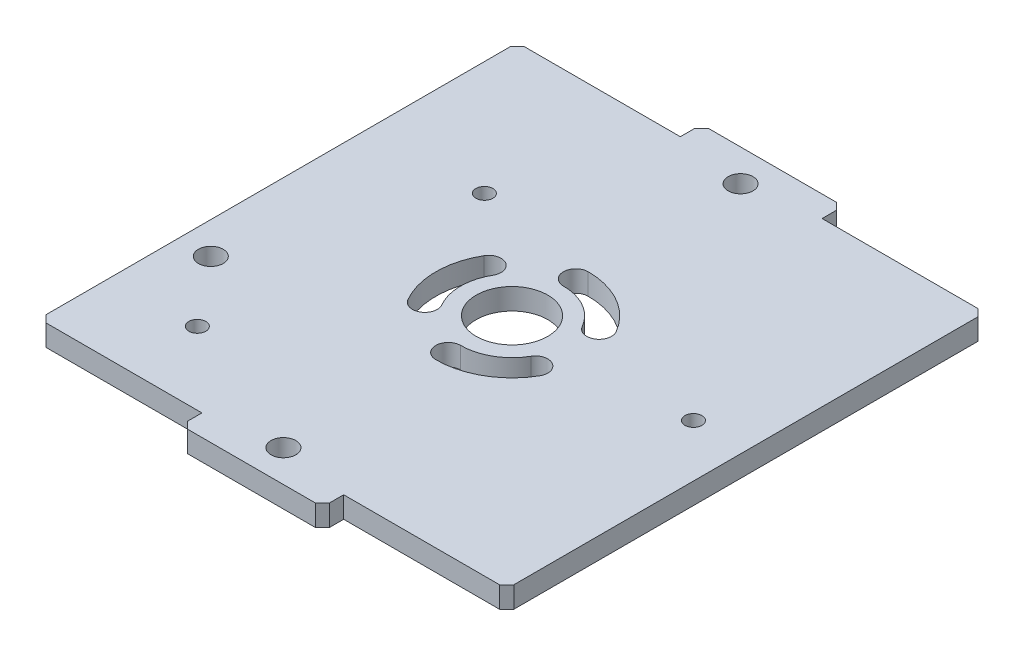
SolidWorks part; units mm, degrees
ref_plane "Front Plane" through (0, 0, 0) normal (0, 0, 1) x (1, 0, 0)
ref_plane "Top Plane" through (0, 0, 0) normal (0, 1, 0) x (1, 0, 0)
ref_plane "Right Plane" through (0, 0, 0) normal (1, 0, 0) x (0, 0, -1)
sketch "Sketch1" plane through (0, 0, 0) normal (0, 1, 0) x (1, 0, 0)
  line L0 (-33, 27.2376) -> (-33, 0)
  line L1 (-33, 0) -> (33, 0)
  line L6 (33, 0) -> (33, 73.5)
  line L7 (33, 73.5) -> (-33, 73.5)
  line L8 (-33, 73.5) -> (-33, 27.2376)
  dimension "D1" = 73.5
  dimension "D2" = 66
extrude "Boss-Extrude1" add sketch "Sketch1" along normal blind 3 separate body
sketch "Croquis13" plane through (0, 3, 0) normal (0, 1, 0) x (1, 0, 0)
  line L0 (0, 73.5) -> (0, 0) construction
  line L1 (-33, 73.5) -> (-10, 73.5)
  line L2 (-33, 73.5) -> (-33, 70.5)
  line L3 (-33, 70.5) -> (-10, 70.5)
  line L4 (-10, 73.5) -> (-10, 70.5)
  line L5 (33, 73.5) -> (10, 73.5)
  line L6 (33, 73.5) -> (33, 70.5)
  line L7 (33, 70.5) -> (10, 70.5)
  line L8 (10, 73.5) -> (10, 70.5)
  line L9 (-33, 0) -> (-10, 0)
  line L10 (-33, 0) -> (-33, 3)
  line L11 (-33, 3) -> (-10, 3)
  line L12 (-10, 0) -> (-10, 3)
  line L13 (33, 0) -> (10, 0)
  line L14 (33, 0) -> (33, 3)
  line L15 (33, 3) -> (10, 3)
  line L16 (10, 0) -> (10, 3)
  line L17 (33, 73.5) -> (-33, 73.5) construction
  dimension "D1" = 20
  dimension "D2" = 3
extrude "Cortar-Extruir3" cut sketch "Croquis13" against normal through all
sketch "Sketch3" plane through (0, 3, 0) normal (0, 1, 0) x (1, 0, 0)
  line L0 (-33, 36.75) -> (33, 36.75) construction
  line L1 (25.6, 36.75) -> (33, 36.75) construction
  line L2 (-33, 70.5) -> (-33, 3) construction
  line L3 (10, 73.5) -> (-10, 73.5) construction
  line L6 (0, 4.5) -> (0, 69) construction
  line L7 (33, 3) -> (33, 70.5) construction
  circle A0 centre (-20.9, 13.25) radius 1.2
  circle A1 centre (0, 36.75) radius 5.05
  circle A2 centre (-16.9, 49.75) radius 1.2
  circle A3 centre (25.6, 36.75) radius 1.2
  circle A7 centre (0, 4.5) radius 1.75
  circle A8 centre (0, 69) radius 1.75
  circle A11 centre (-28.5, 22.75) radius 1.75
  point P23 (0, 36.75)
  dimension "D2" = 4.5
  dimension "D3" = 16.9
  dimension "D5" = 10.1
  dimension "D6" = 14
  dimension "D7" = 23.5
  dimension "D10" = 2.4
  dimension "D11" = 3.5
  dimension "D4" = 20.9
  dimension "D9" = 13
  dimension "D14" = 0
  dimension "D13" = 25.6
  dimension "D8" = 3.5
  dimension "D12" = 4.5
extrude "Cut-Extrude1" cut sketch "Sketch3" against normal up to next
chamfer "Chaflán3" distance 1 angle 45 8 edges at (33, 1.5, -3) (10, 1.5, 0) (-10, 1.5, 0) (-33, 1.5, -3) (33, 1.5, -70.5) (-33, 1.5, -70.5) (10, 1.5, -73.5) (-10, 1.5, -73.5)
sketch "Croquis12" plane through (0, 3, 0) normal (0, 1, 0) x (1, 0, 0)
  line L0 (0, 36.75) -> (-7.7942, 41.25) construction
  line L1 (0, 36.75) -> (-7.7942, 32.25) construction
  line L2 (0, 36.75) -> (-9, 36.75) construction
  line L3 (0, 36.75) -> (4.5, 44.5442) construction
  line L4 (0, 36.75) -> (4.5, 28.9558) construction
  circle A0 centre (0, 36.75) radius 9 construction
  circle A2 centre (-9, 36.75) radius 1.75 construction
  circle A3 centre (4.5, 44.5442) radius 1.75 construction
  circle A4 centre (4.5, 28.9558) radius 1.75 construction
  circle A5 centre (0, 36.75) radius 5.05 construction
  arc A8 (-7.7942, 32.25) -> (-7.7942, 41.25) centre (0, 36.75) cw construction
  arc A9 (-9.3098, 42.125) -> (-9.3098, 31.375) centre (0, 36.75) ccw
  arc A10 (-6.2787, 40.375) -> (-6.2787, 33.125) centre (0, 36.75) ccw
  arc A11 (-6.2787, 40.375) -> (-9.3098, 42.125) centre (-7.7942, 41.25) ccw
  arc A12 (-9.3098, 31.375) -> (-6.2787, 33.125) centre (-7.7942, 32.25) ccw
  arc A13 (0, 45.75) -> (7.7942, 41.25) centre (0, 36.75) cw construction
  arc A14 (9.3098, 42.125) -> (0, 47.5) centre (0, 36.75) ccw
  arc A15 (6.2787, 40.375) -> (0, 44) centre (0, 36.75) ccw
  arc A16 (6.2787, 40.375) -> (9.3098, 42.125) centre (7.7942, 41.25) ccw
  arc A17 (0, 47.5) -> (0, 44) centre (0, 45.75) ccw
  arc A18 (7.7942, 32.25) -> (0, 27.75) centre (0, 36.75) cw construction
  arc A19 (0, 26) -> (9.3098, 31.375) centre (0, 36.75) ccw
  arc A20 (0, 29.5) -> (6.2787, 33.125) centre (0, 36.75) ccw
  arc A21 (0, 29.5) -> (0, 26) centre (0, 27.75) ccw
  arc A22 (9.3098, 31.375) -> (6.2787, 33.125) centre (7.7942, 32.25) ccw
  point P19 (-9, 36.75)
  point P31 (4.5, 44.5442)
  point P38 (4.5, 28.9558)
  point P43 (0, 35)
  dimension "D1" = 18
  dimension "D3" = 3.5
  dimension "D2" = 60
  dimension "D4" = 120
  dimension "D5" = 120
extrude "Cortar-Extruir2" cut sketch "Croquis12" against normal through all
sketch "Croquis1" plane through (0, 3, 0) normal (0, 1, 0) x (1, 0, 0)
  line L0 (-33, 69.5) -> (-33, 4) construction
  line L1 (-22, 57.5) -> (-33, 57.5)
  line L3 (-33, 57.5) -> (-33, 40.5)
  line L4 (-33, 40.5) -> (-22, 40.5)
  line L5 (-33, 40.5) -> (-33.0872, 36.9308)
  line L6 (-22, 40.5) -> (-22, 57.5)
  line L7 (9, 73.5) -> (-9, 73.5) construction
  dimension "D2" = 17
  dimension "D1" = 16
  dimension "D3" = 11
extrude "Cortar-Extruir1" [suppressed] cut sketch "Croquis1" against normal through all
hole_wizard "Taladro roscado M31" [suppressed] positions "Croquis11" profile "Croquis10" tap size "M3" standard "Din"
sketch "Croquis11" plane through (0, 3, 0) normal (0, 1, 0) x (1, 0, 0)
  point P9 (-16.9, 49.75)
  point P19 (25.6, 36.75)
  point P22 (-20.9, 13.25)
sketch "Croquis10" plane through (-16.9, 3, -49.75) normal (1, 0, 0) x (0, 0, 1)
  line L0 (0, 0) -> (0, 3)
  line L1 (0, 3) -> (1.25, 3)
  line L2 (1.25, 3) -> (1.25, 0)
  line L5 (1.25, 0) -> (0, 0)
  line L11 (0, -6.35) -> (0, 107.95) construction
  dimension "Diámetro de perforador para roscar hasta el siguiente" = 2.5
  dimension "Profundidad de perforador para roscar hasta el siguiente" = 3
cosmetic thread "Rosca de taladro1" [suppressed] parameters "D2"=3
cosmetic thread "Rosca de taladro2" [suppressed] parameters "D2"=3
cosmetic thread "Rosca de taladro3" [suppressed] parameters "D2"=3
